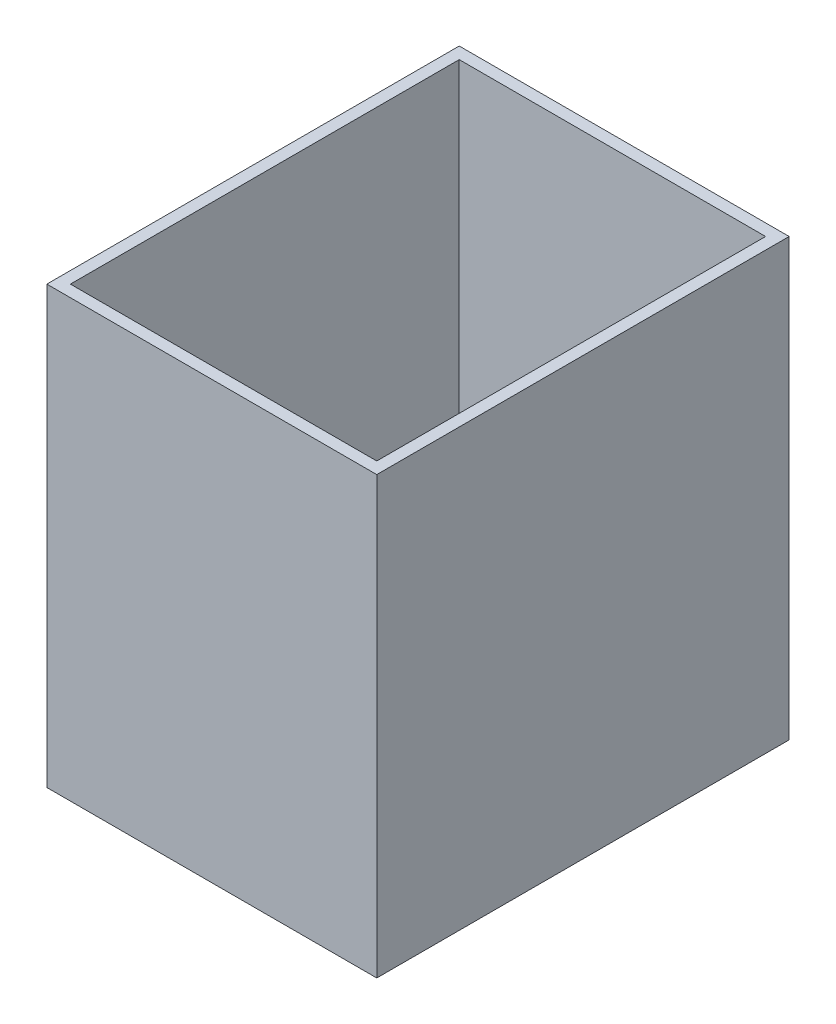
SolidWorks part; units mm, degrees
ref_plane "前基準面" through (0, 0, 0) normal (0, 0, 1) x (1, 0, 0)
ref_plane "上基準面" through (0, 0, 0) normal (0, 1, 0) x (1, 0, 0)
ref_plane "右基準面" through (0, 0, 0) normal (1, 0, 0) x (0, 0, -1)
sketch "草圖1" plane through (0, 0, 0) normal (0, 1, 0) x (1, 0, 0)
  line L0 (-34.1113, 13.5994) -> (-34.1113, -21.4006)
  line L1 (-34.1113, 13.5994) -> (-6.1113, 13.5994)
  line L2 (-6.1113, 13.5994) -> (-6.1113, -21.4006)
  line L3 (-6.1113, -21.4006) -> (-34.1113, -21.4006)
  dimension "D1" = 35
  dimension "D2" = 28
extrude "填料-伸長1" add sketch "草圖1" along normal blind 37
sketch "草圖2" plane through (0, 37, 0) normal (0, 1, 0) x (1, 0, 0)
  line L0 (-20.1113, 13.5994) -> (-20.1113, 12.5994)
  line L1 (-6.1113, 13.5994) -> (-34.1113, 13.5994) construction
  line L2 (-34.1113, -3.9006) -> (-33.1113, -3.9006)
  line L3 (-34.1113, 13.5994) -> (-34.1113, -21.4006) construction
  line L4 (-33.1113, -3.9006) -> (-33.1113, 12.5994)
  line L5 (-33.1113, 12.5994) -> (-7.1113, 12.5994)
  line L6 (-33.1113, -3.9006) -> (-33.1113, -20.4006)
  line L7 (-33.1113, -20.4006) -> (-7.1113, -20.4006)
  line L8 (-7.1113, -20.4006) -> (-7.1113, 12.5994)
  dimension "D1" = 1
  dimension "D2" = 16.5
extrude "除料-伸長1" cut sketch "草圖2" against normal blind 36 contours L7 L8 L5 L4 L6
